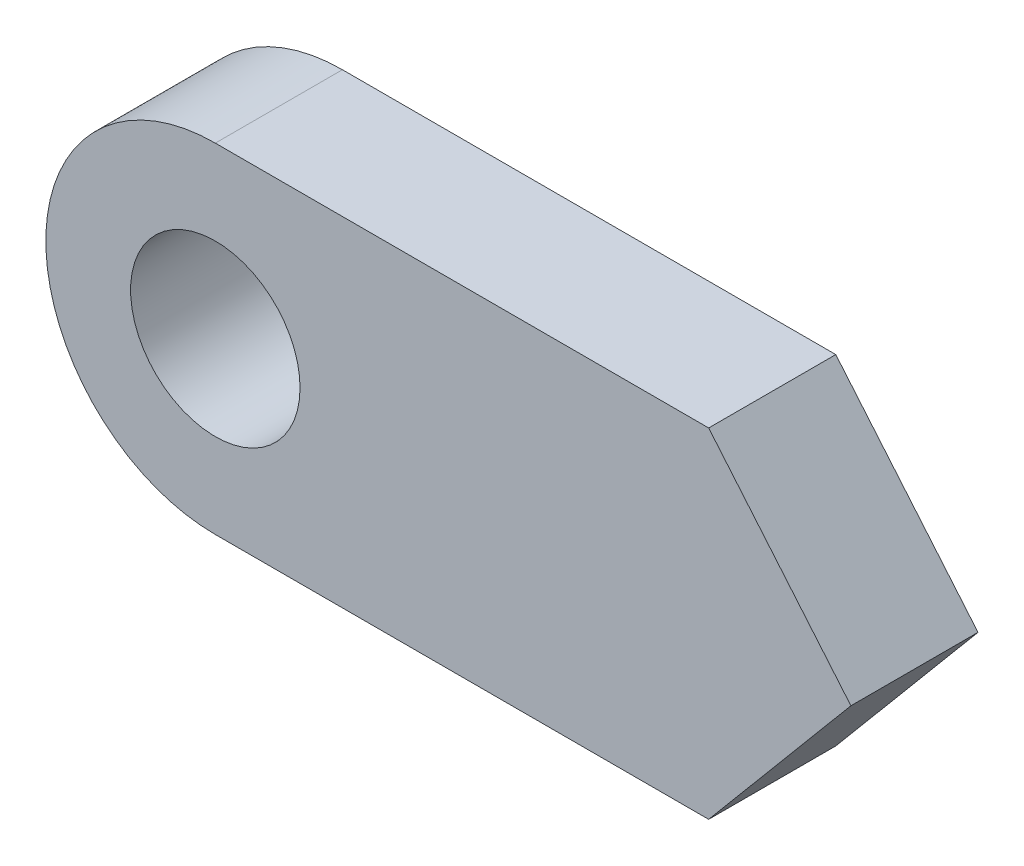
SolidWorks part; units mm, degrees
ref_plane "Front Plane" through (0, 0, 0) normal (0, 0, 1) x (1, 0, 0)
ref_plane "Top Plane" through (0, 0, 0) normal (0, 1, 0) x (1, 0, 0)
ref_plane "Right Plane" through (0, 0, 0) normal (1, 0, 0) x (0, 0, -1)
sketch "Sketch2" plane through (0, 0, 0) normal (0, 0, 1) x (1, 0, 0)
  line L4 (0, 0) -> (116.44, 0)
  line L6 (0, -80) -> (116.44, -80)
  line L7 (150.004, -40) -> (116.44, -80)
  line L8 (116.44, -80) -> (0, -80)
  line L9 (150.004, -40) -> (116.44, 0)
  line L10 (116.44, 0) -> (0, 0)
  arc A0 (0, 0) -> (0, -80) centre (0, -40) ccw
  circle A3 centre (0, -40) radius 20
  dimension "D3" = 40
  dimension "D4" = 130
  dimension "D2" = 116.44
  dimension "D1" = 40
  dimension "D5" = 130
  dimension "D6" = 33.564
  dimension "D7" = 150.004
extrude "Boss-Extrude1" add sketch "Sketch2" along normal blind 30 contours L4 A0 L6 L7 L9 A3
sketch "Sketch3" plane through (0, 0, 30) normal (0, 0, 1) x (1, 0, 0)
  point P0 (0, -40)
